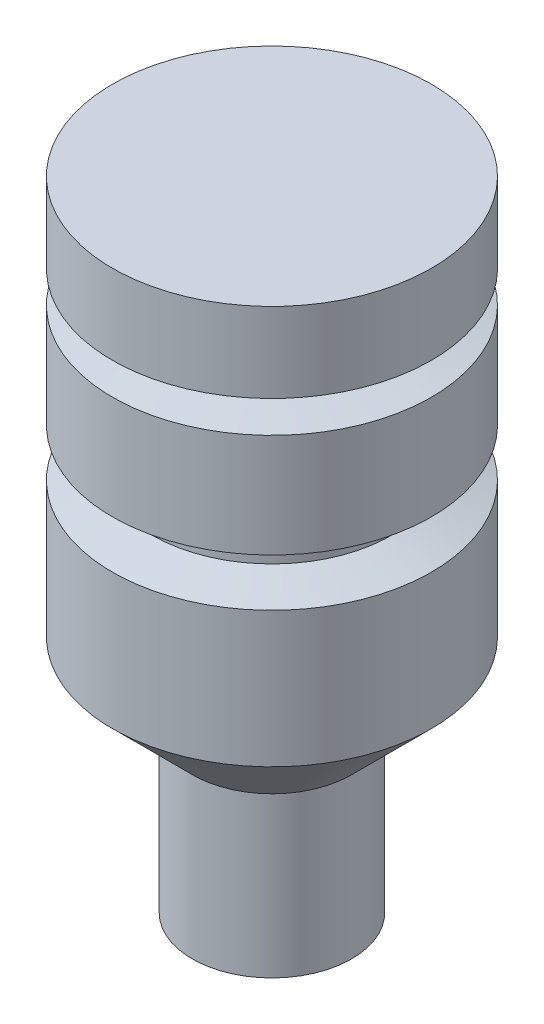
SolidWorks part; units mm, degrees
ref_plane "Front" through (0, 0, 0) normal (0, 0, 1) x (1, 0, 0)
ref_plane "Top" through (0, 0, 0) normal (0, 1, 0) x (1, 0, 0)
ref_plane "Right" through (0, 0, 0) normal (1, 0, 0) x (0, 0, -1)
sketch "Esboço1" plane through (0, 0, 0) normal (0, 0, 1) x (1, 0, 0)
  line L0 (0, 0) -> (0, 40)
  line L1 (0, 40) -> (10, 40)
  line L2 (10, 40) -> (10, 35)
  line L3 (10, 35) -> (7.5, 34.5)
  line L5 (10, 33) -> (10, 26.5)
  line L6 (10, 26.5) -> (7.5, 25.75)
  line L8 (10, 23.5) -> (10, 15)
  line L9 (10, 15) -> (5, 10)
  line L10 (5, 10) -> (5, 0)
  line L11 (5, 0) -> (0, 0)
  line L12 (0, 0) -> (0, 47.7734) construction
  line L13 (7.5, 34.5) -> (7.5, 33.5)
  line L14 (7.5, 33.5) -> (10, 33)
  line L15 (7.5, 25.75) -> (7.5, 24.25)
  line L16 (7.5, 24.25) -> (10, 23.5)
  line L17 (10, 35) -> (10, 33) construction
  line L18 (10, 26.5) -> (10, 23.5) construction
  point P14 (7.5, 25)
  point P17 (7.5, 34)
  point P18 (10, 25)
  point P19 (10, 34)
  dimension "D1" = 10
  dimension "D2" = 20
  dimension "D3" = 15
  dimension "D4" = 1
  dimension "D5" = 40
  dimension "D6" = 25
  dimension "D7" = 34
  dimension "D8" = 2
  dimension "D9" = 135
  dimension "D10" = 10
  dimension "D11" = 3
  dimension "D12" = 1.5
  dimension "D13" = 15
revolve "Revolução1" add sketch "Esboço1" angle 360 about L12
hole_wizard "M3 Gewindebohrung1" positions "3DSketch1" profile "Esboço2" tap size "M3" standard "DIN"
sketch3d "3DSketch1"
  point P0 (0, 0, 0)
sketch "Esboço2" plane through (0, 0, 0) normal (1, 0, 0) x (0, 0, -1)
  line L0 (0, 0) -> (0, 20.7511)
  line L1 (0, 20.7511) -> (1.25, 20)
  line L2 (1.25, 20) -> (1.25, 0)
  line L5 (1.25, 0) -> (0, 0)
  line L10 (0, 20.7511) -> (-1.25, 20) construction
  line L11 (0, -6.35) -> (0, 107.95) construction
  dimension "Tap Drill Dia." = 2.5
  dimension "Tap Drill Depth" = 20
  dimension "Drill Angle" = 118
cosmetic thread "Rosca de furo1" parameters "D1"=6, "D2"=3
